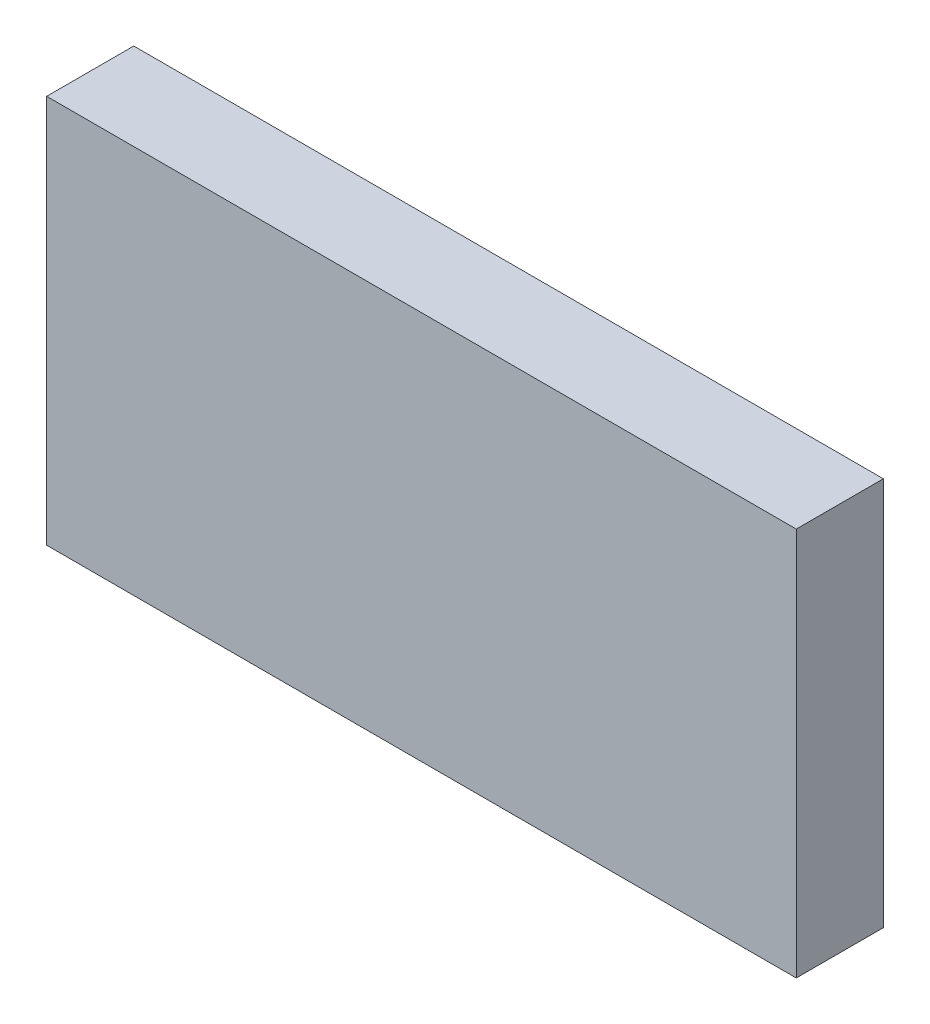
SolidWorks part; units mm, degrees
ref_plane "Front Plane" through (0, 0, 0) normal (0, 0, 1) x (1, 0, 0)
ref_plane "Top Plane" through (0, 0, 0) normal (0, 1, 0) x (1, 0, 0)
ref_plane "Right Plane" through (0, 0, 0) normal (1, 0, 0) x (0, 0, -1)
sketch "Sketch1" plane through (0, 0, 0) normal (0, 1, 0) x (1, 0, 0)
  line L1 (0, 0) -> (24.1, 0)
  line L2 (0, 0) -> (0, 2.8)
  line L3 (0, 2.8) -> (24.1, 2.8)
  line L4 (24.1, 0) -> (24.1, 2.8)
  dimension "D1" = 24.1
  dimension "D2" = 2.8
extrude "Boss-Extrude1" add sketch "Sketch1" along normal blind 12.5
